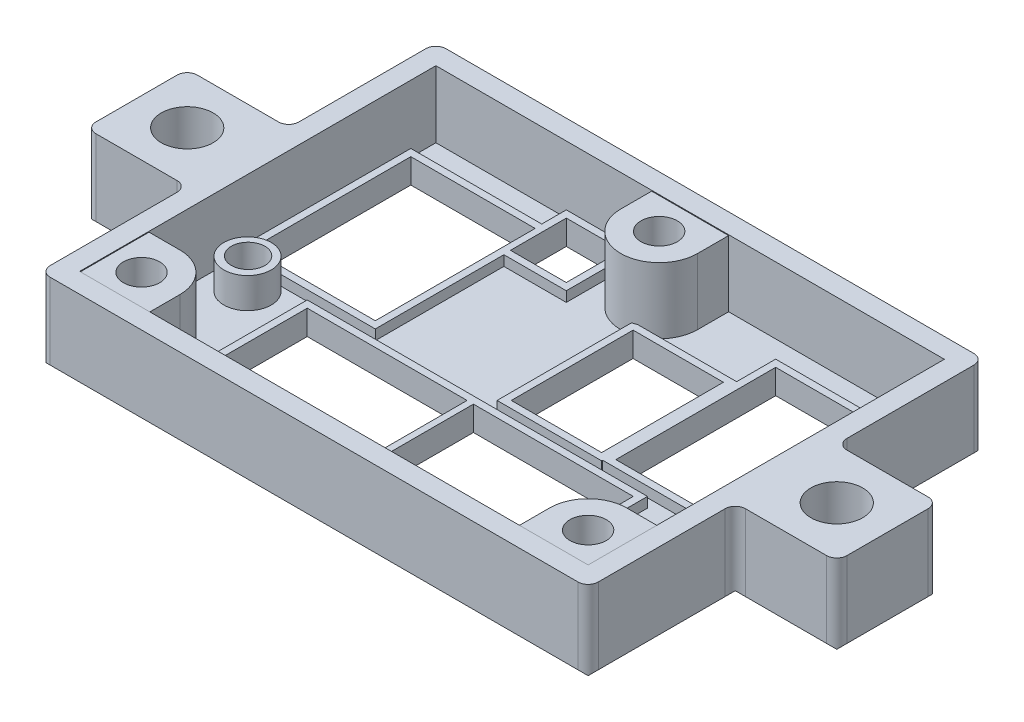
SolidWorks part; units mm, degrees
ref_plane "Front Plane" through (0, 0, 0) normal (0, 0, 1) x (1, 0, 0)
ref_plane "Top Plane" through (0, 0, 0) normal (0, 1, 0) x (1, 0, 0)
ref_plane "Right Plane" through (0, 0, 0) normal (1, 0, 0) x (0, 0, -1)
sketch "Sketch1" plane through (0, 0, 0) normal (0, 1, 0) x (1, 0, 0)
  line L0 (-41.1458, 0) -> (37.3326, 0) construction
  line L1 (-27, -19.5) -> (27, -19.5)
  line L2 (-27, -19.5) -> (-27, 19.5)
  line L3 (-27, 19.5) -> (27, 19.5)
  line L4 (27, -19.5) -> (27, 19.5)
  line L5 (-27, -19.5) -> (27, 19.5) construction
  line L6 (-27, 19.5) -> (27, -19.5) construction
  line L7 (0, 33.589) -> (0, -25.3286) construction
  line L8 (-37, -5) -> (-27, -5)
  line L9 (-37, -5) -> (-37, 5)
  line L10 (-37, 5) -> (-27, 5)
  line L11 (-27, -5) -> (-27, 5)
  line L12 (-37, -5) -> (-27, 5) construction
  line L13 (-37, 5) -> (-27, -5) construction
  line L14 (37, -5) -> (37, 5)
  line L15 (37, 5) -> (27, 5)
  line L16 (37, -5) -> (27, -5)
  circle A0 centre (-32, 0) radius 2.5527
  circle A1 centre (32, 0) radius 2.5527
  point P0 (0, 0)
  point P8 (-32, 0)
  dimension "D5" = 5.1054
  dimension "D1" = 54
  dimension "D2" = 39
  dimension "D3" = 10
  dimension "D4" = 10
extrude "Boss-Extrude1" add sketch "Sketch1" along normal blind 8 contours L1 L4 L3 L2 | L16 L14 L15 L4 A1 | L10 L9 L8 L2 A0
sketch "Sketch2" plane through (0, 8, 0) normal (0, 1, 0) x (1, 0, 0)
  line L0 (0, 27.4) -> (0, -30.8783) construction
  line L1 (-42.9811, 0) -> (41.0645, 0) construction
  line L3 (-25.05, -17.55) -> (25.05, -17.55)
  line L4 (-25.05, -17.55) -> (-25.05, 17.55)
  line L5 (-25.05, 17.55) -> (25.05, 17.55)
  line L6 (25.05, -17.55) -> (25.05, 17.55)
  line L7 (-25.05, -17.55) -> (25.05, 17.55) construction
  line L8 (-25.05, 17.55) -> (25.05, -17.55) construction
  point P5 (0, 0)
  dimension "D1" = 50.1
  dimension "D2" = 35.1
extrude "Cut-Extrude1" cut sketch "Sketch2" against normal blind 0.0762
sketch "Sketch3" plane through (0, 7.9238, 0) normal (0, 1, 0) x (1, 0, 0)
  line L0 (0, 25.6254) -> (0, -24.9156) construction
  line L1 (-43.478, 0) -> (41.2775, 0) construction
  line L2 (-5.4043, 14.5) -> (7.1001, 14.5) construction
  line L3 (-3.79, 14.5) -> (-3.79, 17.55)
  line L4 (25.05, 17.55) -> (-25.05, 17.55) construction
  line L5 (3.79, 14.5) -> (3.79, 17.55)
  line L7 (-22, -6.9215) -> (-22, -24.9156) construction
  line L8 (-15.6235, -14.5) -> (-28.7086, -14.5) construction
  line L9 (-18.21, -14.5) -> (-18.21, -17.55)
  line L10 (-25.05, -17.55) -> (25.05, -17.55) construction
  line L11 (-22, -10.71) -> (-25.05, -10.71)
  line L12 (-25.05, 17.55) -> (-25.05, -17.55) construction
  line L13 (-18.21, -17.55) -> (18.21, -17.55)
  line L14 (-25.05, -10.71) -> (-25.05, 17.55)
  line L15 (-25.05, 17.55) -> (-3.79, 17.55)
  line L16 (18.21, -14.5) -> (18.21, -17.55)
  line L17 (22, -10.71) -> (25.05, -10.71)
  line L18 (25.05, -10.71) -> (25.05, 17.55)
  line L19 (25.05, 17.55) -> (3.79, 17.55)
  arc A0 (-3.79, 14.5) -> (3.79, 14.5) centre (0, 14.5) ccw
  arc A1 (-18.21, -14.5) -> (-22, -10.71) centre (-22, -14.5) ccw
  arc A2 (18.21, -14.5) -> (22, -10.71) centre (22, -14.5) cw
  point P31 (0, -17.55)
  dimension "D1" = 7.58
  dimension "D3" = 7.58
  dimension "D2" = 14.5
  dimension "D4" = 22
  dimension "D5" = 14.5
extrude "Cut-Extrude2" cut sketch "Sketch3" against normal blind 6.5
sketch "Sketch4" plane through (0, 7.9238, 0) normal (0, 1, 0) x (1, 0, 0)
  line L0 (0, 26.0262) -> (0, -25.2956) construction
  line L1 (-42.2713, 0) -> (43.691, 0) construction
  circle A0 centre (0, 14.5) radius 1.56
  circle A1 centre (-22, -14.5) radius 1.56
  circle A2 centre (22, -14.5) radius 1.56
  dimension "D1" = 3.12
  dimension "D2" = 14.5
  dimension "D3" = 22
  dimension "D4" = 14.5
extrude "Cut-Extrude3" cut sketch "Sketch4" against normal through all
sketch "Sketch5" plane through (0, 7.9238, 0) normal (0, 1, 0) x (1, 0, 0)
  line L0 (0, 25.6254) -> (0, -24.7736) construction
  line L1 (-41.9164, 0) -> (40.1417, 0) construction
  circle A0 centre (0, 14.5) radius 1.79
  circle A1 centre (-22, -14.5) radius 1.79
  circle A2 centre (22, -14.5) radius 1.79
  dimension "D1" = 3.58
extrude "Cut-Extrude4" cut sketch "Sketch5" against normal blind 2.92
sketch "Sketch6" plane through (0, 1.4238, 0) normal (0, 1, 0) x (1, 0, 0)
  line L0 (25.05, -17.55) -> (25.05, 17.55) construction
  line L1 (24.1, 14.13) -> (11.85, 14.13)
  line L2 (24.1, 14.13) -> (24.1, -1.62)
  line L3 (24.1, -1.62) -> (11.85, -1.62)
  line L4 (11.85, 14.13) -> (11.85, -1.62)
  line L5 (25.05, 17.55) -> (-25.05, 17.55) construction
  line L6 (-18.21, -17.55) -> (18.21, -17.55) construction
  line L7 (15.85, -3.9) -> (0.1, -3.9)
  line L8 (15.85, -3.9) -> (15.85, -16.4)
  line L9 (15.85, -16.4) -> (0.1, -16.4)
  line L10 (0.1, -3.9) -> (0.1, -16.4)
  line L11 (25.05, -17.55) -> (25.05, -10.71) construction
  line L12 (0, 23.4777) -> (0, -37.1578) construction
  line L13 (-11.85, 14.13) -> (-11.85, -1.62)
  line L14 (-24.1, -1.62) -> (-11.85, -1.62)
  line L15 (-24.1, 14.13) -> (-24.1, -1.62)
  line L16 (-24.1, 14.13) -> (-11.85, 14.13)
  line L17 (-3.79, 17.55) -> (-25.05, 17.55) construction
  line L18 (-0.525, -3.9) -> (-16.275, -3.9)
  line L19 (-0.525, -3.9) -> (-0.525, -16.4)
  line L20 (-0.525, -16.4) -> (-16.275, -16.4)
  line L21 (-16.275, -3.9) -> (-16.275, -16.4)
  line L22 (-11.2, 16.55) -> (-5.7, 16.55)
  line L23 (-11.2, 16.55) -> (-11.2, 11.05)
  line L24 (-11.2, 11.05) -> (-5.7, 11.05)
  line L25 (-5.7, 16.55) -> (-5.7, 11.05)
  dimension "D1" = 0.95
  dimension "D2" = 12.25
  dimension "D3" = 15.75
  dimension "D4" = 3.42
  dimension "D5" = 12.5
  dimension "D6" = 15.75
  dimension "D7" = 1.15
  dimension "D8" = 9.2
  dimension "D9" = 0.625
  dimension "D10" = 12.5
  dimension "D11" = 15.75
  dimension "D12" = 5.5
  dimension "D13" = 5.5
  dimension "D14" = 1
  dimension ".65" = 0.65
extrude "Cut-Extrude5" cut sketch "Sketch6" against normal through all
sketch "Sketch7" plane through (0, 1.4238, 0) normal (0, 1, 0) x (1, 0, 0)
  line L0 (11.85, 14.13) -> (11.85, -1.62) construction
  line L1 (10.55, 10.28) -> (1.65, 10.28)
  line L2 (10.55, 10.28) -> (10.55, -1.72)
  line L3 (10.55, -1.72) -> (1.65, -1.72)
  line L4 (1.65, 10.28) -> (1.65, -1.72)
  line L5 (11.85, -1.62) -> (24.1, -1.62) construction
  dimension "D1" = 8.9
  dimension "D2" = 12
  dimension "D3" = 1.3
  dimension "D4" = 0.1
extrude "Cut-Extrude6" cut sketch "Sketch7" against normal through all
sketch "Sketch9" plane through (0, 1.4238, 0) normal (0, 1, 0) x (1, 0, 0)
  line L0 (-25.05, -17.55) -> (-18.21, -17.55) construction
  line L1 (-25.05, 17.55) -> (-25.05, -17.55) construction
  circle A0 centre (-21.65, -4.35) radius 1.651
  dimension "D3" = 3.302
  dimension "D1" = 13.2
  dimension "D2" = 3.4
chamfer "Chamfer1" distance 0.5 angle 45 12 edges at (27, 0, -12.25) (27, 0, 12.25) (0, 0, 19.5) (-27, 0, 12.25) (0, 0, -19.5) (-27, 0, -12.25) (32, 0, -5) (37, 0, 0) (32, 0, 5) (-32, 0, 5) (-32, 0, -5) (-37, 0, 0)
extrude "Cut-Extrude8" cut sketch "Sketch9" against normal through all
sketch "Sketch10" plane through (0, 1.4238, 0) normal (0, 1, 0) x (1, 0, 0)
  circle A0 centre (-21.65, -4.35) radius 1.651
  circle A1 centre (-21.65, -4.4065) radius 2.3375
  dimension "D1" = 4.675
  dimension "D2" = 3.302
extrude "Boss-Extrude2" add sketch "Sketch10" along normal blind 3
sketch "Sketch11" plane through (0, 1.4238, 0) normal (0, 1, 0) x (1, 0, 0)
  line L0 (15.85, -16.4) -> (15.85, -3.9) construction
  line L1 (0.1, -16.4) -> (15.85, -16.4) construction
  line L2 (-16.275, -16.4) -> (-0.525, -16.4) construction
  line L3 (-16.275, -3.9) -> (-16.275, -16.4) construction
  line L4 (-0.525, -3.9) -> (-16.275, -3.9) construction
  line L5 (0.1, -3.9) -> (0.1, -16.4) construction
  line L6 (-0.525, -16.4) -> (-0.525, -3.9) construction
  line L7 (15.85, -3.9) -> (0.1, -3.9) construction
  line L8 (11.85, -1.62) -> (24.1, -1.62) construction
  line L9 (24.1, -1.62) -> (24.1, 14.13) construction
  line L10 (24.1, 14.13) -> (11.85, 14.13) construction
  line L11 (11.85, 14.13) -> (11.85, -1.62) construction
  line L12 (1.65, -1.72) -> (10.55, -1.72) construction
  line L13 (10.55, -1.72) -> (10.55, 10.28) construction
  line L14 (10.55, 10.28) -> (1.65, 10.28) construction
  line L15 (1.65, 10.28) -> (1.65, -1.72) construction
  line L16 (-11.2, 16.55) -> (-11.2, 11.05) construction
  line L17 (-5.7, 16.55) -> (-11.2, 16.55) construction
  line L18 (-5.7, 11.05) -> (-5.7, 16.55) construction
  line L19 (-11.2, 11.05) -> (-5.7, 11.05) construction
  line L20 (-24.1, 14.13) -> (-24.1, -1.62) construction
  line L21 (-24.1, -1.62) -> (-11.85, -1.62) construction
  line L22 (-11.85, -1.62) -> (-11.85, 14.13) construction
  line L23 (-11.85, 14.13) -> (-24.1, 14.13) construction
  line L24 (15.85, -16.4) -> (15.85, -3.9)
  line L25 (0.1, -16.4) -> (15.85, -16.4)
  line L26 (-16.275, -16.4) -> (-0.525, -16.4)
  line L27 (-16.275, -3.9) -> (-16.275, -16.4)
  line L28 (-0.525, -3.9) -> (-16.275, -3.9)
  line L29 (0.1, -3.9) -> (0.1, -16.4)
  line L30 (-0.525, -16.4) -> (-0.525, -3.9)
  line L31 (15.85, -3.9) -> (0.1, -3.9)
  line L32 (11.85, -1.62) -> (24.1, -1.62)
  line L33 (24.1, -1.62) -> (24.1, 14.13)
  line L34 (24.1, 14.13) -> (11.85, 14.13)
  line L35 (11.85, 14.13) -> (11.85, -1.62)
  line L36 (1.65, -1.72) -> (10.55, -1.72)
  line L37 (10.55, -1.72) -> (10.55, 10.28)
  line L38 (10.55, 10.28) -> (1.65, 10.28)
  line L39 (1.65, 10.28) -> (1.65, -1.72)
  line L40 (-11.2, 16.55) -> (-11.2, 11.05)
  line L41 (-5.7, 16.55) -> (-11.2, 16.55)
  line L42 (-5.7, 11.05) -> (-5.7, 16.55)
  line L43 (-11.2, 11.05) -> (-5.7, 11.05)
  line L44 (-24.1, 14.13) -> (-24.1, -1.62)
  line L45 (-24.1, -1.62) -> (-11.85, -1.62)
  line L46 (-11.85, -1.62) -> (-11.85, 14.13)
  line L47 (-11.85, 14.13) -> (-24.1, 14.13)
  line L48 (-11.15, -2.32) -> (-11.15, 10.35)
  line L49 (-11.9, 14.83) -> (-24.8, 14.83)
  line L50 (-24.8, 14.83) -> (-24.8, -2.32)
  line L51 (-24.8, -2.32) -> (-11.15, -2.32)
  line L53 (-5, 10.35) -> (-5, 17.25)
  line L54 (-5, 17.25) -> (-11.9, 17.25)
  line L55 (-11.9, 17.25) -> (-11.9, 14.83)
  line L56 (0.95, 10.98) -> (0.95, -2.42)
  line L57 (0.95, -2.42) -> (11.25, -2.42)
  line L58 (11.25, -2.42) -> (11.25, -2.32)
  line L59 (11.15, 10.98) -> (0.95, 10.98)
  line L60 (11.15, 14.83) -> (11.15, 10.98)
  line L61 (11.25, -2.32) -> (24.8, -2.32)
  line L62 (24.8, -2.32) -> (24.8, 14.83)
  line L63 (24.8, 14.83) -> (11.15, 14.83)
  line L64 (16.55, -3.2) -> (0.175, -3.2)
  line L66 (0.175, -17.1) -> (16.55, -17.1)
  line L67 (16.55, -17.1) -> (16.55, -3.2)
  line L68 (0.175, -3.2) -> (-16.975, -3.2)
  line L69 (-16.975, -3.2) -> (-16.975, -17.1)
  line L70 (-16.975, -17.1) -> (0.175, -17.1)
  line L72 (-11.15, 10.35) -> (-5, 10.35)
  line L73 (-11.15, 14.83) -> (-24.8, 14.83) construction
  line L74 (-11.15, -2.32) -> (-11.15, 14.83) construction
  line L76 (-11.9, 17.25) -> (-11.9, 10.35) construction
  line L77 (-11.9, 10.35) -> (-5, 10.35) construction
  line L78 (11.25, 10.98) -> (0.95, 10.98) construction
  line L79 (11.25, -2.42) -> (11.25, 10.98) construction
  line L80 (11.15, 14.83) -> (11.15, -2.32) construction
  line L81 (11.15, -2.32) -> (24.8, -2.32) construction
  line L82 (-0.6, -3.2) -> (-0.6, -17.1) construction
  line L83 (0.175, -17.1) -> (0.175, -3.2) construction
  line L84 (16.55, -3.2) -> (-0.6, -3.2) construction
  line L85 (-0.6, -17.1) -> (16.55, -17.1) construction
  dimension "D1" = 0.7
extrude "Boss-Extrude3" add sketch "Sketch11" along normal blind 1
fillet "Fillet1" radius 1 12 edges at (-27, 4.25, -5) (-37, 4.25, 5) (-37, 4.25, -5) (-27, 4.25, 5) (-27, 4.25, 19.5) (27, 4.25, 5) (27, 4.25, 19.5) (-27, 4.25, -19.5) (37, 4.25, 5) (37, 4.25, -5) (27, 4.25, -5) (27, 4.25, -19.5)
